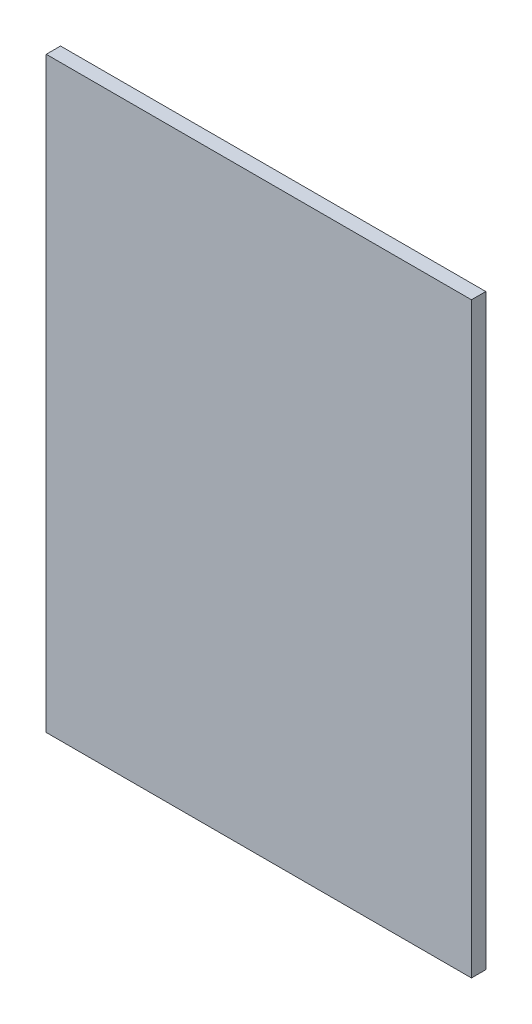
SolidWorks part; units mm, degrees
ref_plane "Front Plane" through (0, 0, 0) normal (0, 0, 1) x (1, 0, 0)
ref_plane "Top Plane" through (0, 0, 0) normal (0, 1, 0) x (1, 0, 0)
ref_plane "Right Plane" through (0, 0, 0) normal (1, 0, 0) x (0, 0, -1)
sketch "Sketch1" plane through (0, 0, -13.061) normal (0, 0, 1) x (1, 0, 0)
  line L0 (64.4251, 30.1885) -> (64.4251, -38.8233) construction
  line L5 (64.4251, -38.8233) -> (14.4633, -38.8233) construction
  line L6 (14.4633, -38.8233) -> (14.4633, 30.1885) construction
  line L7 (14.4633, 30.1885) -> (23.4549, 30.1885) construction
  line L8 (64.4251, 30.1885) -> (64.4251, -38.8233)
  line L9 (64.4251, -38.8233) -> (14.4633, -38.8233)
  line L10 (14.4633, -38.8233) -> (14.4633, 30.1885)
  line L11 (14.4633, 30.1885) -> (23.4549, 30.1885)
  line L13 (64.4251, -38.8233) -> (14.4633, -38.8233)
  line L14 (64.4251, -38.8233) -> (64.4251, 30.1885)
  line L15 (64.4251, 30.1885) -> (14.4633, 30.1885)
  line L16 (14.4633, -38.8233) -> (14.4633, 30.1885)
  line M17 (15.3777, 28.0803) -> (23.4549, 28.0803)
  line M18 (23.4549, 28.0803) -> (23.4549, 30.1885)
  line M19 (23.4549, 30.1885) -> (14.4633, 30.1885)
  line M20 (14.4633, 30.1885) -> (14.4633, -38.8233)
  line M21 (14.4633, -38.8233) -> (64.4251, -38.8233)
  line M22 (64.4251, -38.8233) -> (64.4251, 30.1885)
  line M23 (64.4251, 30.1885) -> (55.2049, 30.1885)
  line M24 (55.2049, 30.1885) -> (55.2049, 28.0803)
  line M25 (55.2049, 28.0803) -> (63.5107, 28.0803)
  line M26 (63.5107, 28.0803) -> (63.5107, -37.9089)
  line M27 (63.5107, -37.9089) -> (15.3777, -37.9089)
  line M28 (15.3777, -37.9089) -> (15.3777, 28.0803)
extrude "Boss-Extrude1" add sketch "Sketch1" along normal offset from surface (1.6822 mm away) 4.4 contours M28 M17 M18 M19 M20 M21 M22 M23 M24 M25 M26 M27 | L15 M24 M18 M17 M28 M27 M26 M25
